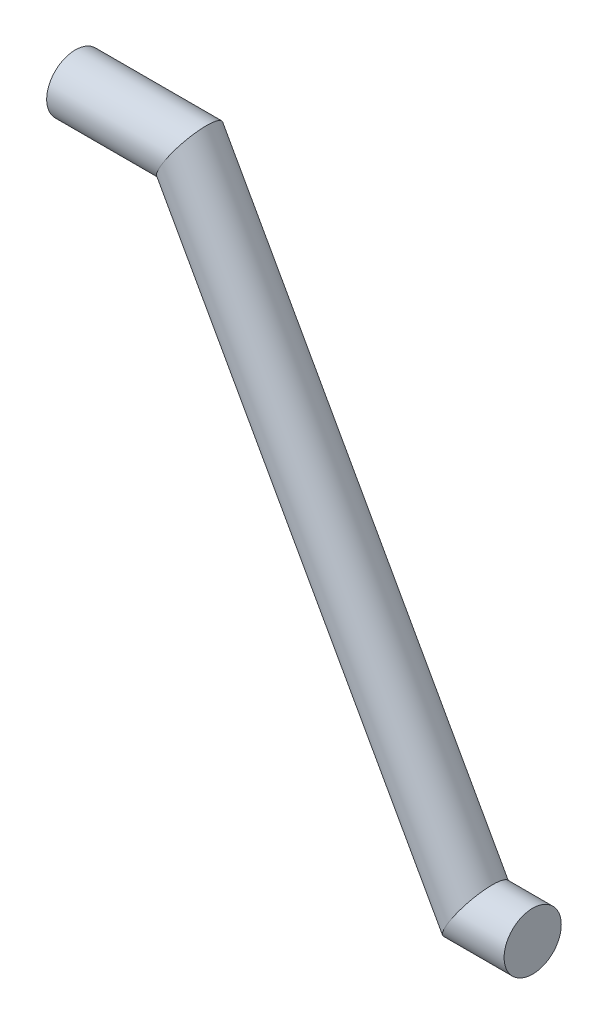
SolidWorks part; units mm, degrees
ref_plane "Front Plane" through (0, 0, 0) normal (0, 0, 1) x (1, 0, 0)
ref_plane "Top Plane" through (0, 0, 0) normal (0, 1, 0) x (1, 0, 0)
ref_plane "Right Plane" through (0, 0, 0) normal (1, 0, 0) x (0, 0, -1)
sketch "Sketch1" plane through (0, 0, 0) normal (1, 0, 0) x (0, 0, -1)
  circle A0 centre (0, 0) radius 25
  dimension "D1" = 50
sketch "Sketch2" plane through (0, 0, 0) normal (0, 0, 1) x (1, 0, 0)
  line L0 (0, 0) -> (100, 0)
  line L1 (0, -25) -> (0, 25) construction
  line L2 (100, 0) -> (350, -450)
  line L3 (350, -450) -> (400, -450)
  line L4 (100, 0) -> (100, -522.7742) construction
  line L5 (350, -450) -> (100, -450) construction
  dimension "D1" = 100
  dimension "D2" = 450
  dimension "D3" = 50
  dimension "D4" = 250
sweep "Sweep1" add profiles "Sketch1" path "Sketch2"
